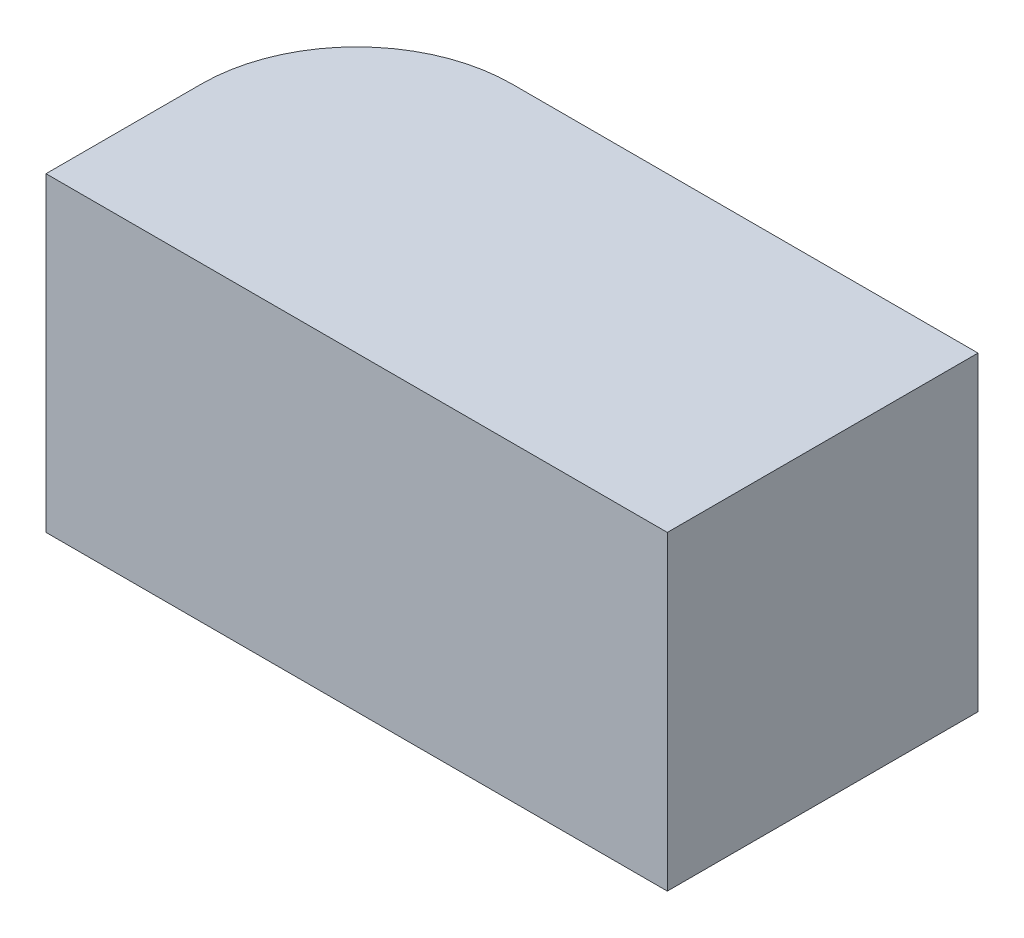
SolidWorks part; units mm, degrees
ref_plane "Přední rovina" through (0, 0, 0) normal (0, 0, 1) x (1, 0, 0)
ref_plane "Horní rovina" through (0, 0, 0) normal (0, 1, 0) x (1, 0, 0)
ref_plane "Pravá rovina" through (0, 0, 0) normal (1, 0, 0) x (0, 0, -1)
sketch "Sketch1" plane through (0, 0, 0) normal (0, 1, 0) x (1, 0, 0)
  line L0 (0, 0) -> (30, 0)
  line L1 (-10, -20) -> (30, -20)
  line L2 (-10, -20) -> (-10, -10)
  line L4 (30, -20) -> (30, 0)
  arc A0 (-10, -10) -> (0, 0) centre (0, -10) cw
  dimension "D1" = 10
  dimension "D2" = 40
  dimension "D3" = 20
extrude "Boss-Extrude1" add sketch "Sketch1" along normal blind 20
equation "\"R\"= 10'Radius"
equation "\"H\"= 20'Extrude height"
equation "\"D1@Boss-Extrude1\"=\"H\""
equation "\"D2@Sketch1\"=\"R\"*4"
equation "\"D3@Sketch1\"=\"R\"*2mm"
equation "\"D1@Sketch1\"=\"R\""
